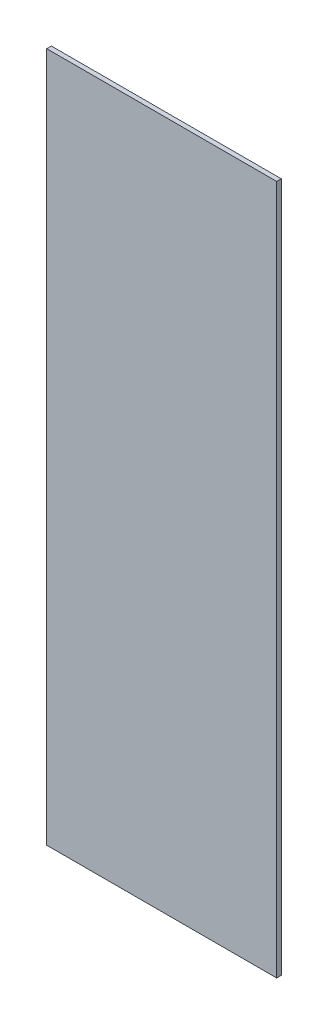
SolidWorks part; units mm, degrees
ref_plane "Front Plane" through (0, 0, 0) normal (0, 0, 1) x (1, 0, 0)
ref_plane "Top Plane" through (0, 0, 0) normal (0, 1, 0) x (1, 0, 0)
ref_plane "Right Plane" through (0, 0, 0) normal (1, 0, 0) x (0, 0, -1)
sketch "Sketch1" plane through (0, 0, 0) normal (0, 0, 1) x (1, 0, 0)
  line L1 (0, 0) -> (100, 0)
  line L2 (0, 0) -> (0, -300)
  line L3 (0, -300) -> (100, -300)
  line L4 (100, 0) -> (100, -300)
  dimension "D1" = 100
  dimension "D2" = 300
extrude "Boss-Extrude1" add sketch "Sketch1" along normal blind 2
